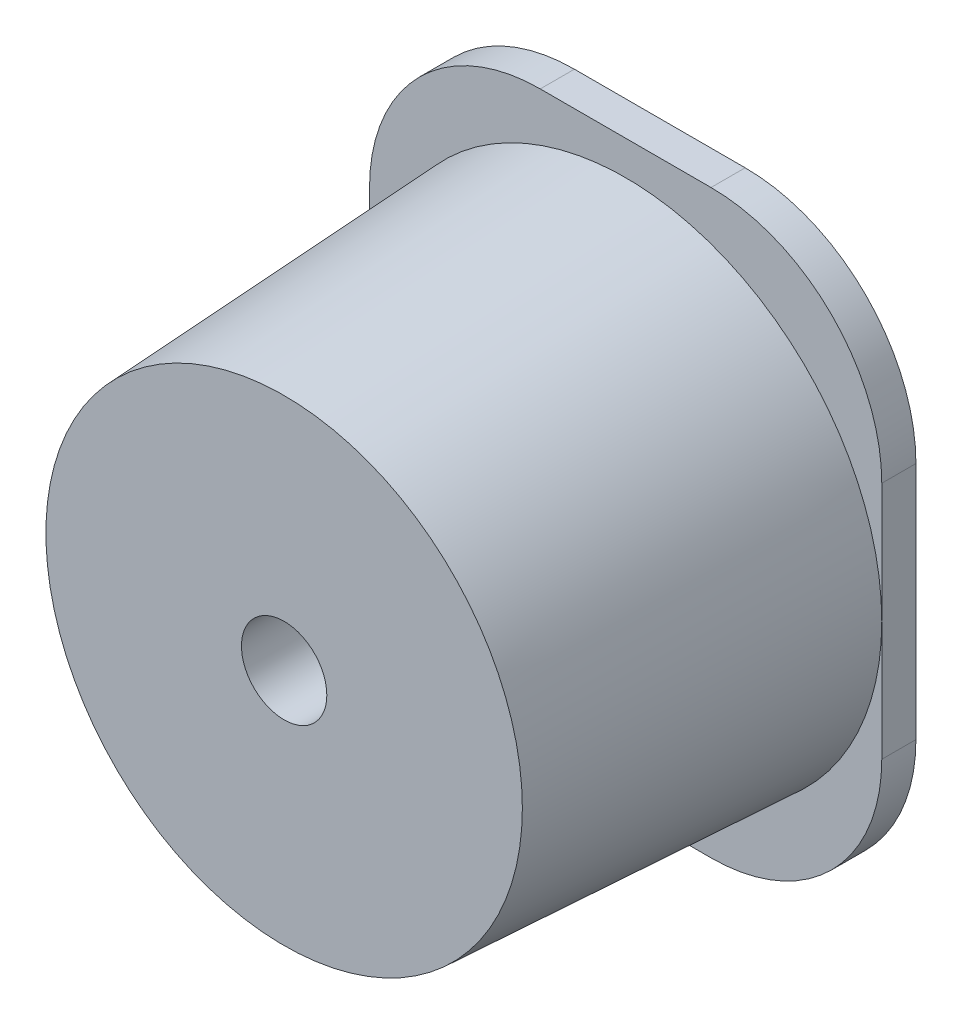
SolidWorks part; units mm, degrees
ref_plane "Front Plane" through (0, 0, 0) normal (0, 0, 1) x (1, 0, 0)
ref_plane "Top Plane" through (0, 0, 0) normal (0, 1, 0) x (1, 0, 0)
ref_plane "Right Plane" through (0, 0, 0) normal (1, 0, 0) x (0, 0, -1)
sketch "Sketch1" plane through (0, 0, 0) normal (0, 0, 1) x (1, 0, 0)
  circle A0 centre (0, 0) radius 75
  dimension "D1" = 150
extrude "Boss-Extrude1" add sketch "Sketch1" along normal blind 100 draft 3
sketch "Sketch2" plane through (0, 0, 0) normal (0, 0, -1) x (-1, 0, 0)
  line L1 (-25, -85) -> (25, -85)
  line L2 (-75, -35) -> (-75, 35)
  line L3 (-25, 85) -> (25, 85)
  line L4 (75, -35) -> (75, 35)
  line L5 (-75, -85) -> (75, 85) construction
  line L6 (-75, 85) -> (75, -85) construction
  arc A0 (-25, -85) -> (-75, -35) centre (-25, -35) cw
  arc A1 (25, -85) -> (75, -35) centre (25, -35) ccw
  arc A2 (25, 85) -> (75, 35) centre (25, 35) cw
  arc A3 (-75, 35) -> (-25, 85) centre (-25, 35) cw
  point P0 (0, 0)
  dimension "D3" = 50
  dimension "D1" = 150
  dimension "D2" = 170
extrude "Boss-Extrude2" add sketch "Sketch2" along normal blind 10
sketch "Sketch3" plane through (0, 0, 100) normal (0, 0, 1) x (1, 0, 0)
  circle A0 centre (0, 0) radius 12.5
  dimension "D1" = 25
extrude "Cut-Extrude1" cut sketch "Sketch3" against normal blind 50
